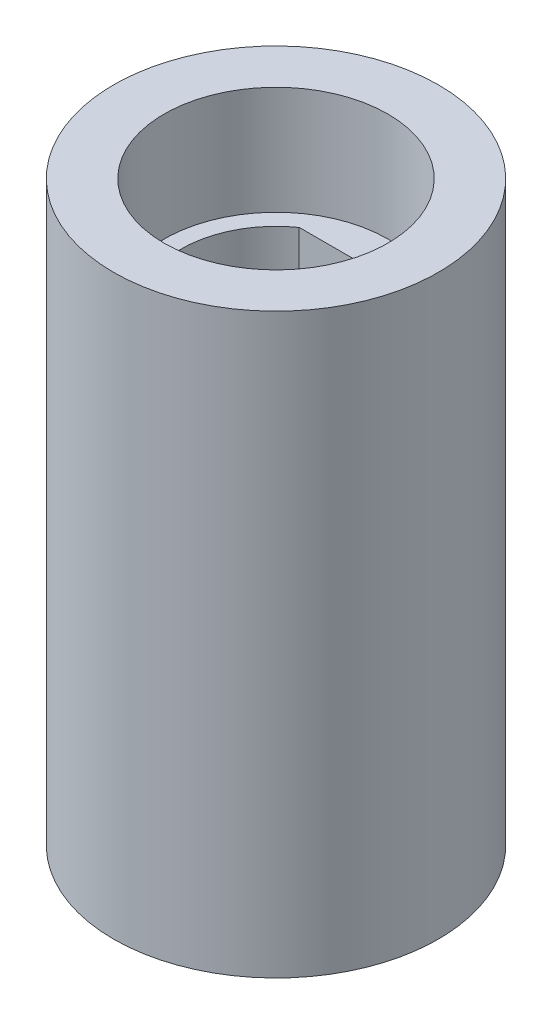
SolidWorks part; units mm, degrees
ref_plane "Front Plane" through (0, 0, 0) normal (0, 0, 1) x (1, 0, 0)
ref_plane "Top Plane" through (0, 0, 0) normal (0, 1, 0) x (1, 0, 0)
ref_plane "Right Plane" through (0, 0, 0) normal (1, 0, 0) x (0, 0, -1)
sketch "Sketch1" plane through (0, 0, 0) normal (0, 1, 0) x (1, 0, 0)
  line L0 (0, 2.625) -> (0, 2.15) construction
  line L1 (1.506, 2.15) -> (-1.506, 2.15)
  circle A0 centre (0, 0) radius 4.5
  arc A1 (-1.506, 2.15) -> (1.506, 2.15) centre (0, 0) ccw
  point P9 (0, 2.15)
  dimension "D1" = 5.25
  dimension "D3" = 9
  dimension "D2" = 2.15
extrude "Boss-Extrude1" add sketch "Sketch1" along normal blind 16
sketch "Sketch2" plane through (0, 16, 0) normal (0, 1, 0) x (1, 0, 0)
  circle A0 centre (0, 0) radius 3.1
  dimension "D1" = 6.2
extrude "Cut-Extrude1" cut sketch "Sketch2" against normal blind 3
